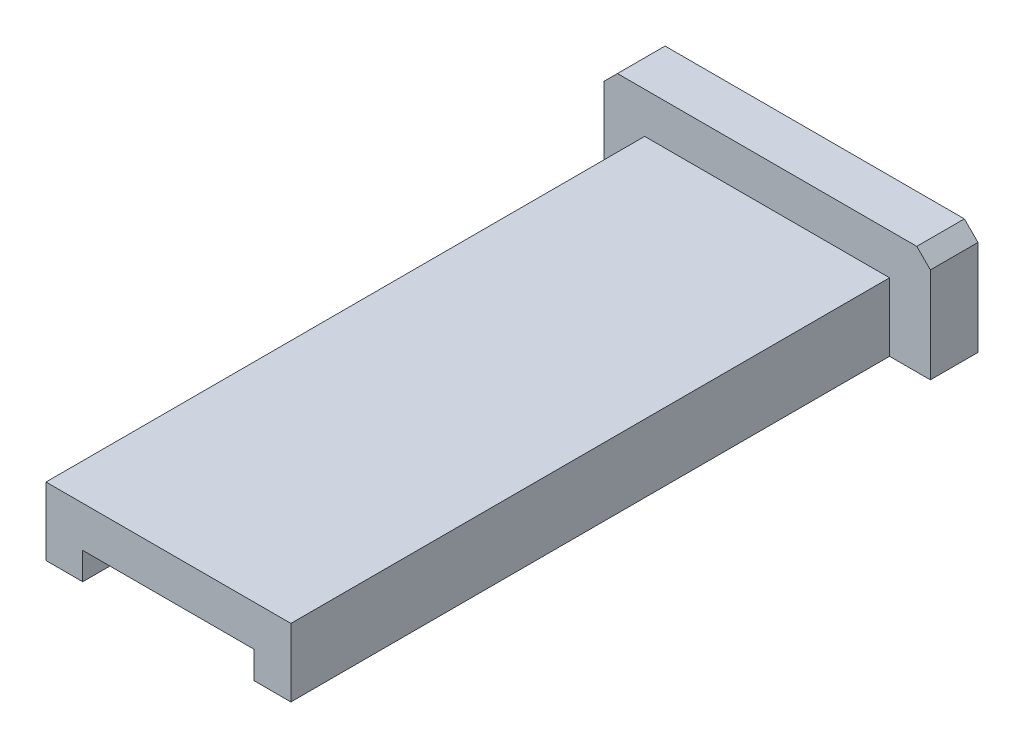
SolidWorks part; units mm, degrees
material "CA"
ref_plane "前视基准面" through (0, 0, 0) normal (0, 0, 1) x (1, 0, 0)
ref_plane "上视基准面" through (0, 0, 0) normal (0, 1, 0) x (1, 0, 0)
ref_plane "右视基准面" through (0, 0, 0) normal (1, 0, 0) x (0, 0, -1)
sketch "草图1" plane through (0, 0, 0) normal (0, 0, 1) x (1, 0, 0)
  line L1 (-9, -2.5) -> (9, -2.5)
  line L2 (-9, -2.5) -> (-9, 2.5)
  line L3 (-9, 2.5) -> (9, 2.5)
  line L4 (9, -2.5) -> (9, 2.5)
  line L5 (-9, -2.5) -> (9, 2.5) construction
  line L6 (-9, 2.5) -> (9, -2.5) construction
  point P0 (0, 0)
  dimension "D1" = 18
  dimension "D2" = 5
extrude "凸台-拉伸1" add sketch "草图1" along normal blind 47.5
sketch "草图2" plane through (0, 0, 0) normal (0, 0, -1) x (-1, 0, 0)
  line L0 (12, -2.5) -> (12, 5.5)
  line L1 (-12, -2.5) -> (12, -2.5)
  line L2 (-12, -2.5) -> (-12, 5.5)
  line L3 (-12, 5.5) -> (12, 5.5)
  line L4 (0, -2.5) -> (0, 5.5) construction
  line L5 (9, -2.5) -> (-9, -2.5) construction
  dimension "D1" = 8
  dimension "D2" = 24
extrude "凸台-拉伸2" add sketch "草图2" against normal blind 3.5
sketch "草图3" plane through (0, 0, 0) normal (0, 0, -1) x (-1, 0, 0)
  line L0 (12, -2.5) -> (-12, -2.5) construction
  line L1 (-6.3, -2.5) -> (6.3, -2.5)
  line L2 (-6.3, -2.5) -> (-6.3, -0.5)
  line L3 (-6.3, -0.5) -> (6.3, -0.5)
  line L4 (0, -2.5) -> (0, -0.5) construction
  line L5 (6.3, -2.5) -> (6.3, -0.5)
  dimension "D1" = 12.6
  dimension "D2" = 2
extrude "切除-拉伸1" cut sketch "草图3" against normal through all
chamfer "倒角1" distance 1 angle 45 2 edges at (12, 5.5, 1.75) (-12, 5.5, 1.75)
